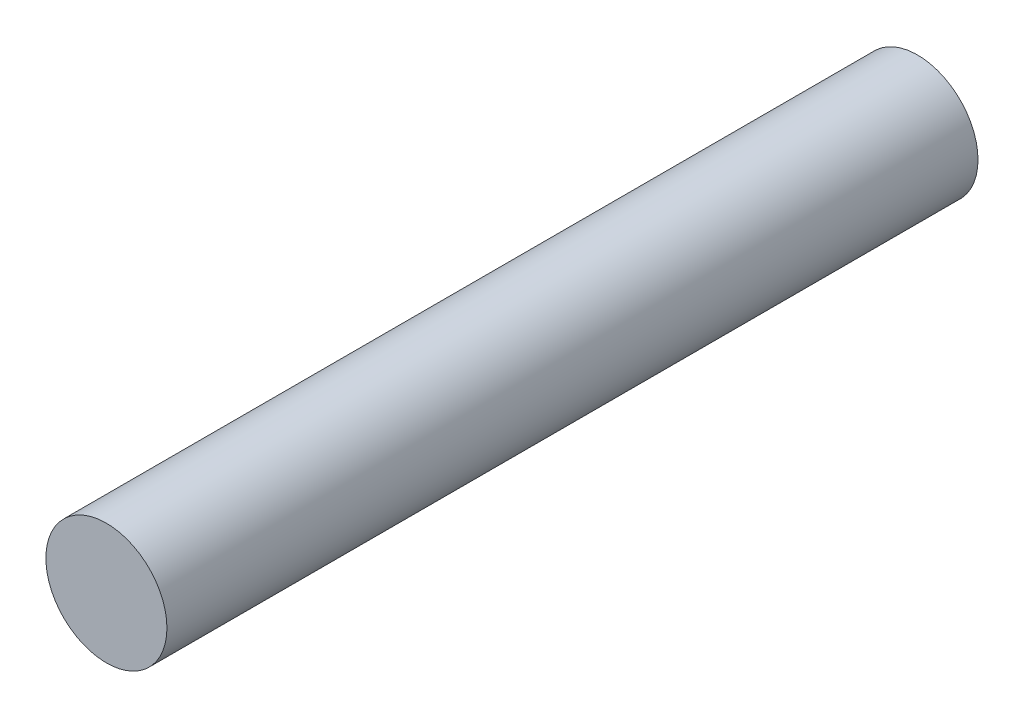
SolidWorks part; units mm, degrees
ref_plane "Front Plane" through (0, 0, 0) normal (0, 0, 1) x (1, 0, 0)
ref_plane "Top Plane" through (0, 0, 0) normal (0, 1, 0) x (1, 0, 0)
ref_plane "Right Plane" through (0, 0, 0) normal (1, 0, 0) x (0, 0, -1)
sketch "Sketch1" plane through (0, 0, 0) normal (0, 0, 1) x (1, 0, 0)
  circle A0 centre (0, 0) radius 5
  dimension "D1" = 10
extrude "Boss-Extrude1" add sketch "Sketch1" along normal blind 67
